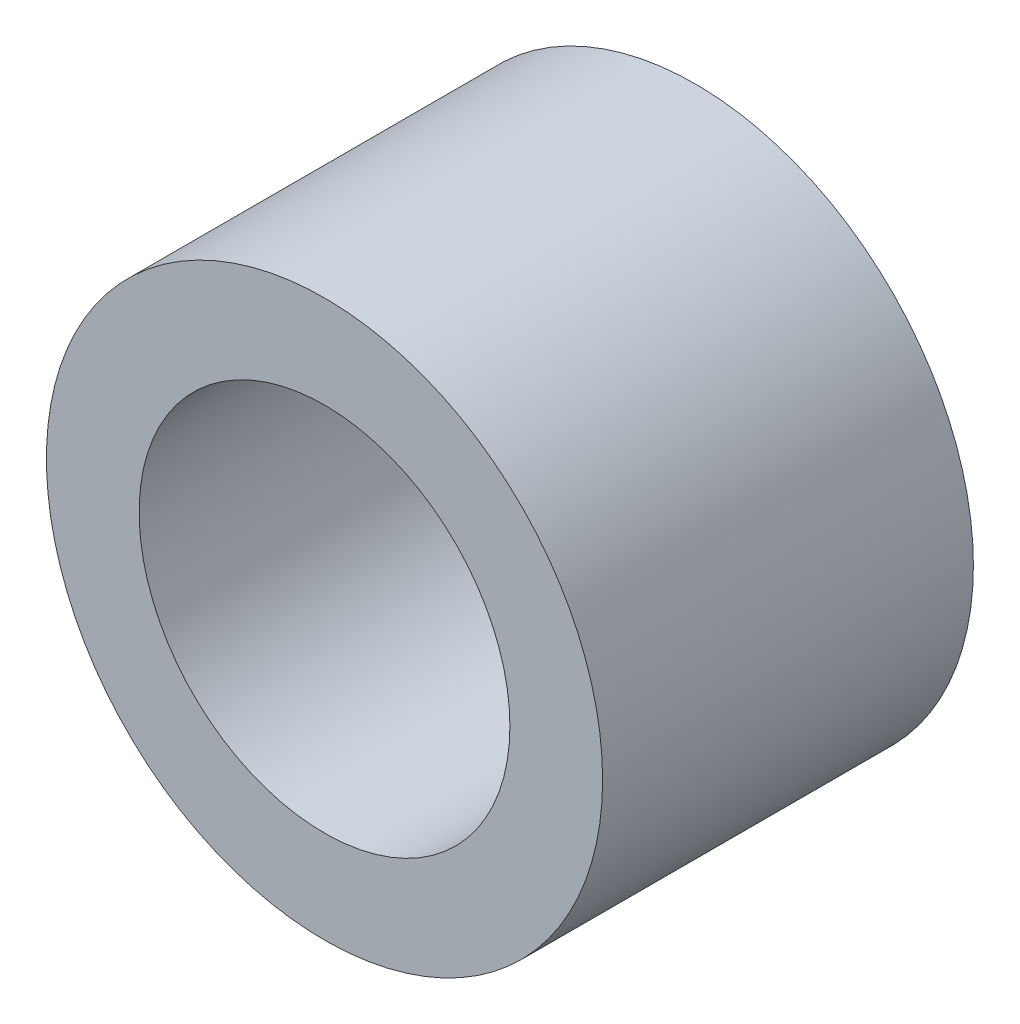
SolidWorks part; units mm, degrees
ref_plane "Front Plane" through (0, 0, 0) normal (0, 0, 1) x (1, 0, 0)
ref_plane "Top Plane" through (0, 0, 0) normal (0, 1, 0) x (1, 0, 0)
ref_plane "Right Plane" through (0, 0, 0) normal (1, 0, 0) x (0, 0, -1)
sketch "Sketch1" plane through (0, 0, 0) normal (0, 0, 1) x (1, 0, 0)
  circle A0 centre (0, 0) radius 25.4
  circle A1 centre (0, 0) radius 38.1
  dimension "D1" = 50.8
  dimension "D2" = 76.2
extrude "Boss-Extrude1" add sketch "Sketch1" against normal blind 50.8 from offset 25.4
